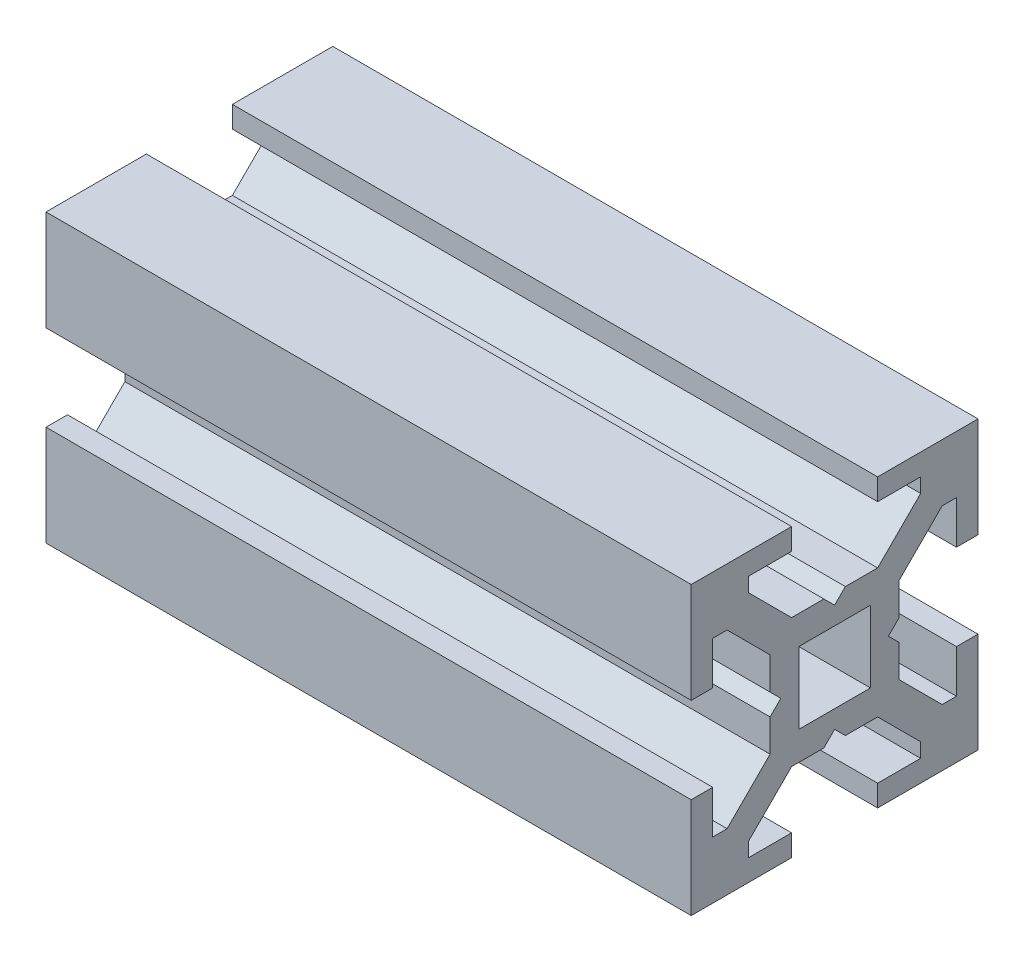
SolidWorks part; units mm, degrees
ref_plane "Front Plane" through (0, 0, 0) normal (0, 0, 1) x (1, 0, 0)
ref_plane "Top Plane" through (0, 0, 0) normal (0, 1, 0) x (1, 0, 0)
ref_plane "Right Plane" through (0, 0, 0) normal (1, 0, 0) x (0, 0, -1)
sketch "Sketch1" plane through (0, 0, 0) normal (1, 0, 0) x (0, 0, -1)
  line L0 (-27.451, 0) -> (27.451, 0) construction
  line L5 (0, -31.0196) -> (0, 26.6275) construction
  line L6 (-10, 10) -> (-3, 10)
  line L7 (-10, 10) -> (-10, 3)
  line L8 (-3, 10) -> (-3, 8.5)
  line L11 (-8.5, 3) -> (-10, 3)
  line L17 (3, 8.5) -> (3, 10)
  line L18 (-0.75, -4.5) -> (0, -3.75)
  line L22 (-3, 8.5) -> (-6, 8.5)
  line L23 (-8.5, 3) -> (-8.5, 6)
  line L24 (-8.5, 6) -> (-7.5, 6)
  line L25 (-6, 8.5) -> (-6, 7.5)
  line L26 (-7.5, 6) -> (-4.5, 3)
  line L27 (-6, 7.5) -> (-3, 4.5)
  line L29 (4.5, 3) -> (4.5, 0.75)
  line L30 (3, -4.5) -> (0.75, -4.5)
  line L61 (-4.5, 0.75) -> (-3.75, 0)
  line L62 (3, 4.5) -> (0.75, 4.5)
  line L65 (-4.5, -3) -> (-4.5, -0.75)
  line L66 (-2.5, -2.5) -> (2.5, -2.5)
  line L67 (-2.5, -2.5) -> (-2.5, 2.5)
  line L68 (-8.5, -3) -> (-10, -3)
  line L73 (4.5, -0.75) -> (3.75, 0)
  line L75 (-4.5, -0.75) -> (-3.75, 0)
  line L76 (-8.5, -3) -> (-8.5, -6)
  line L77 (-7.5, -6) -> (-4.5, -3)
  line L78 (-6, -7.5) -> (-3, -4.5)
  line L79 (-3, -8.5) -> (-6, -8.5)
  line L80 (-3, -10) -> (-3, -8.5)
  line L81 (-10, -10) -> (-3, -10)
  line L82 (-10, -10) -> (-10, -3)
  line L83 (-6, -8.5) -> (-6, -7.5)
  line L84 (-8.5, -6) -> (-7.5, -6)
  line L85 (4.5, 0.75) -> (3.75, 0)
  line L86 (10, -10) -> (10, -3)
  line L87 (8.5, -3) -> (10, -3)
  line L88 (8.5, -3) -> (8.5, -6)
  line L89 (8.5, -6) -> (7.5, -6)
  line L90 (6, -8.5) -> (6, -7.5)
  line L91 (10, -10) -> (3, -10)
  line L92 (3, -10) -> (3, -8.5)
  line L93 (3, -8.5) -> (6, -8.5)
  line L94 (6, -7.5) -> (3, -4.5)
  line L95 (7.5, -6) -> (4.5, -3)
  line L96 (6, 7.5) -> (3, 4.5)
  line L97 (7.5, 6) -> (4.5, 3)
  line L98 (8.5, 6) -> (7.5, 6)
  line L99 (8.5, 3) -> (10, 3)
  line L100 (8.5, 3) -> (8.5, 6)
  line L101 (10, 10) -> (10, 3)
  line L102 (6, 8.5) -> (6, 7.5)
  line L103 (3, 8.5) -> (6, 8.5)
  line L104 (10, 10) -> (3, 10)
  line L105 (4.5, -0.75) -> (4.5, -3)
  line L106 (-4.5, 0.75) -> (-4.5, 3)
  line L107 (-0.75, 4.5) -> (0, 3.75)
  line L108 (0, 3.75) -> (0.75, 4.5)
  line L109 (-0.75, 4.5) -> (-3, 4.5)
  line L110 (-2.5, 2.5) -> (2.5, 2.5)
  line L111 (2.5, -2.5) -> (2.5, 2.5)
  line L112 (-2.5, -2.5) -> (2.5, 2.5) construction
  line L113 (-2.5, 2.5) -> (2.5, -2.5) construction
  line L114 (0, -3.75) -> (0.75, -4.5)
  line L115 (-0.75, -4.5) -> (-3, -4.5)
  point P4 (0, 0)
  point P5 (0, 0)
  point P12 (-4.5, 4.5)
  point P13 (4.5, -4.5)
  point P14 (4.5, 4.5)
  point P15 (-4.5, -4.5)
  point P16 (0, 0)
  point P25 (0, 0)
  dimension "D1" = 20
  dimension "D2" = 20
  dimension "D3" = 7
  dimension "D4" = 1.5
  dimension "D5" = 5
  dimension "D7" = 3
  dimension "D8" = 1
  dimension "D9" = 45
  dimension "D10" = 45
  dimension "D11" = 45
  dimension "D6" = 6
  dimension "D12" = 1.5
  dimension "D13" = 1.5
  dimension "D14" = 2.25
extrude "Boss-Extrude2" add sketch "Sketch1" along normal blind 45
